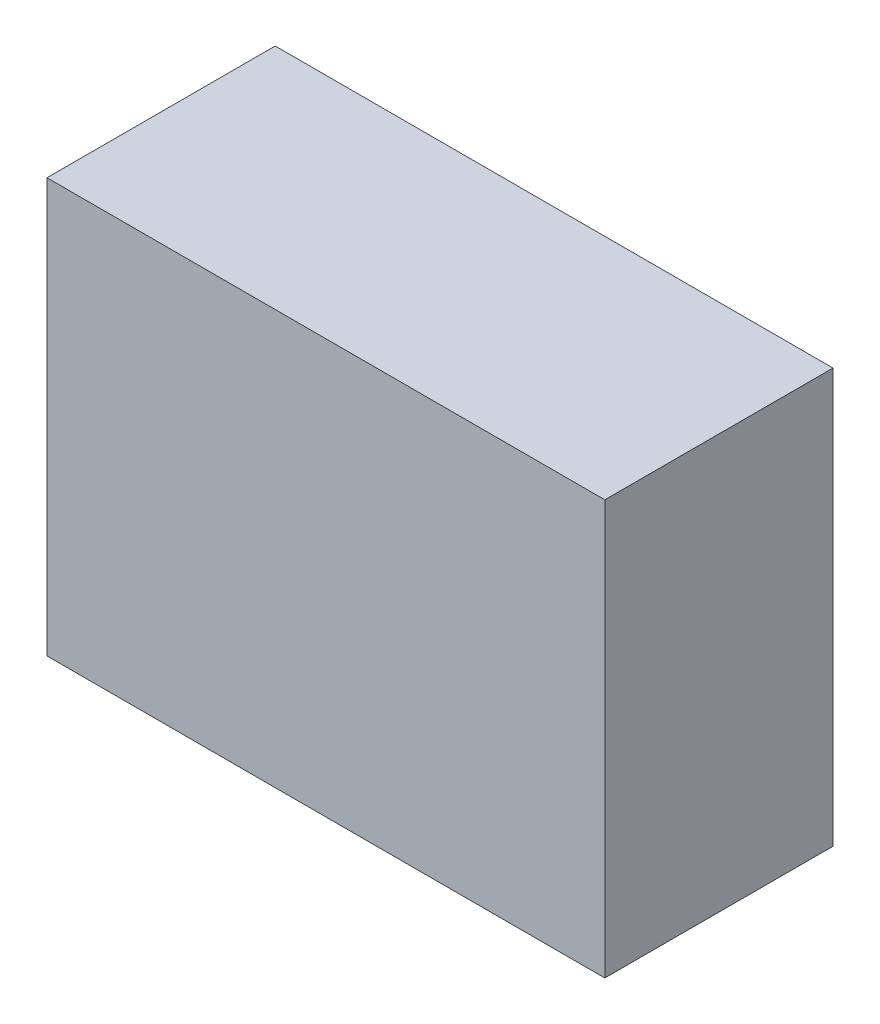
SolidWorks part; units mm, degrees
ref_plane "Front Plane" through (0, 0, 0) normal (0, 0, 1) x (1, 0, 0)
ref_plane "Top Plane" through (0, 0, 0) normal (0, 1, 0) x (1, 0, 0)
ref_plane "Right Plane" through (0, 0, 0) normal (1, 0, 0) x (0, 0, -1)
sketch "Sketch1" plane through (0, 0, 0) normal (0, 0, 1) x (1, 0, 0)
  line L1 (-33, -24.5) -> (33, -24.5)
  line L2 (-33, -24.5) -> (-33, 24.5)
  line L3 (-33, 24.5) -> (33, 24.5)
  line L4 (33, -24.5) -> (33, 24.5)
  line L5 (-33, -24.5) -> (33, 24.5) construction
  line L6 (-33, 24.5) -> (33, -24.5) construction
extrude "Envelope" add sketch "Sketch1" along normal blind 27
